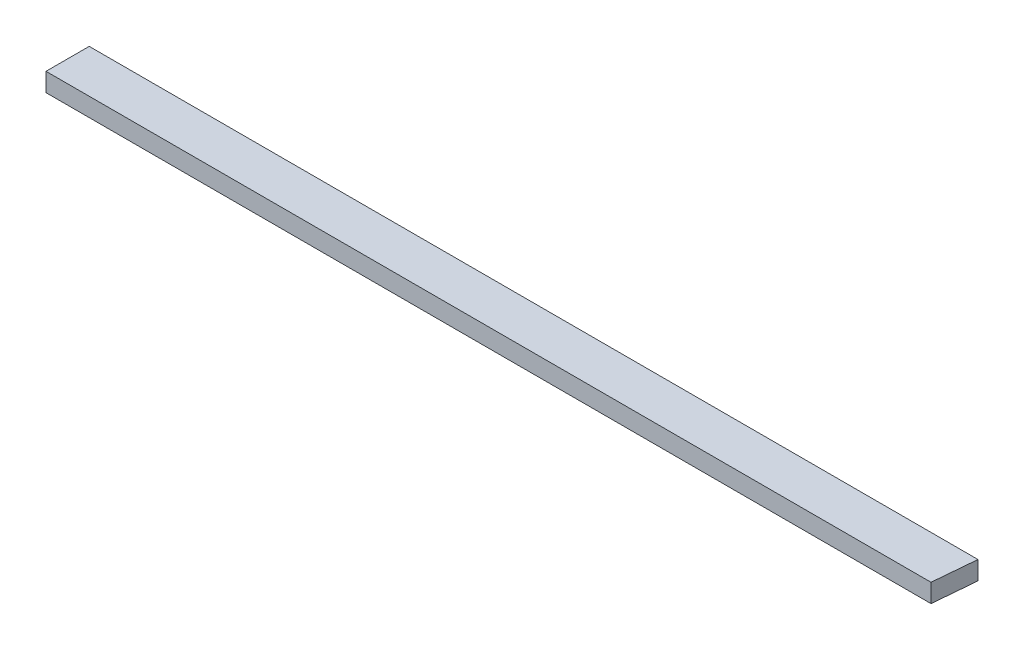
SolidWorks part; units mm, degrees
ref_plane "Front Plane" through (0, 0, 0) normal (0, 0, 1) x (1, 0, 0)
ref_plane "Top Plane" through (0, 0, 0) normal (0, 1, 0) x (1, 0, 0)
ref_plane "Right Plane" through (0, 0, 0) normal (1, 0, 0) x (0, 0, -1)
sketch "Sketch1" plane through (0, 0, 0) normal (0, 1, 0) x (1, 0, 0)
  line L0 (1828.8, 88.9) -> (1821.0223, 0)
  line L1 (0, 0) -> (1821.0223, 0)
  line L2 (0, 0) -> (0, 88.9)
  line L3 (0, 88.9) -> (1828.8, 88.9)
  line L5 (1304.7533, 88.9) -> (1304.7533, 0) construction
  line L6 (1223.2914, 88.9) -> (1223.2914, 0) construction
  line L7 (1141.8296, 88.9) -> (1141.8296, 0) construction
  line L8 (1060.3677, 88.9) -> (1060.3677, 0) construction
  line L9 (978.9058, 88.9) -> (978.9058, 0) construction
  line L10 (897.444, 88.9) -> (897.444, 0) construction
  line L11 (815.9821, 88.9) -> (815.9821, 0) construction
  line L12 (734.5202, 88.9) -> (734.5202, 0) construction
  line L13 (653.0584, 88.9) -> (653.0584, 0) construction
  line L14 (571.5965, 88.9) -> (571.5965, 0) construction
  line L15 (490.1347, 88.9) -> (490.1347, 0) construction
  line L16 (408.6728, 88.9) -> (408.6728, 0) construction
  line L17 (327.2109, 88.9) -> (327.2109, 0) construction
  line L18 (245.7491, 88.9) -> (245.7491, 0) construction
  line L19 (164.2872, 88.9) -> (164.2872, 0) construction
  line L20 (82.8253, 88.9) -> (82.8253, 0) construction
  line L22 (1.3635, 88.9) -> (1.3635, 0) [skipped]
  dimension "D1" = 88.9
  dimension "D2" = 1828.8
  dimension "D3" = 85
  dimension "D4" = 17
  dimension "D5" = 524.0467
  dimension "D6" = 605.5086
  dimension "D7" = 686.9704
  dimension "D8" = 768.4323
  dimension "D9" = 849.8942
  dimension "D10" = 931.356
  dimension "D11" = 1012.8179
  dimension "D12" = 1094.2798
  dimension "D13" = 1175.7416
  dimension "D14" = 81.4619
  dimension "D15" = 1257.2035
  dimension "D16" = 1338.6653
  dimension "D17" = 1420.1272
  dimension "D18" = 1501.5891
  dimension "D20" = 1745.9747
extrude "Boss-Extrude1" add sketch "Sketch1" against normal blind 38.1
